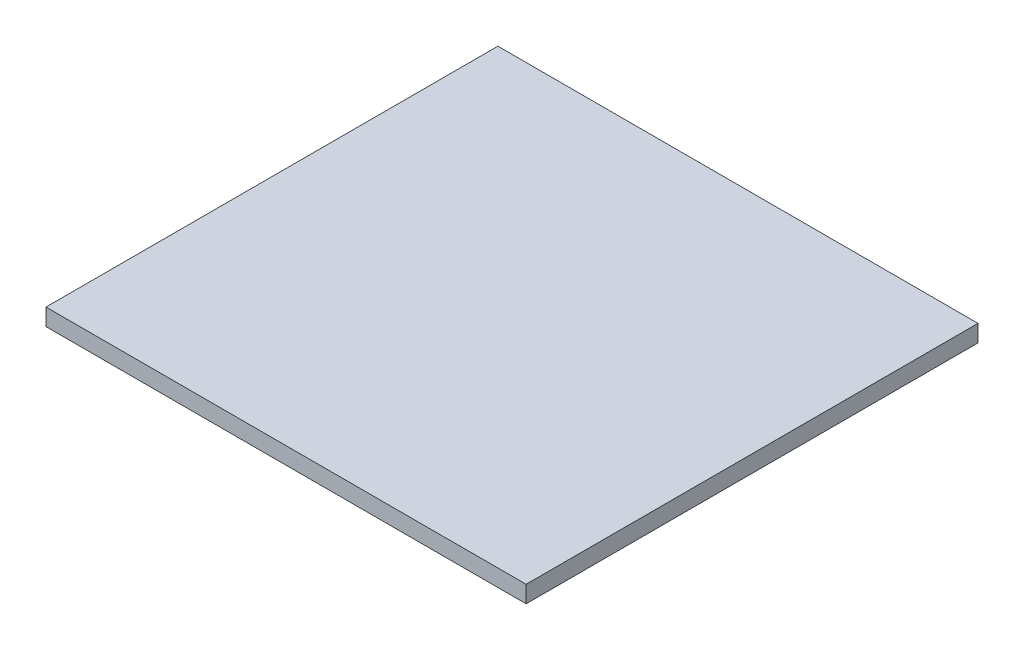
SolidWorks part; units mm, degrees
ref_plane "Front Plane" through (0, 0, 0) normal (0, 0, 1) x (1, 0, 0)
ref_plane "Top Plane" through (0, 0, 0) normal (0, 1, 0) x (1, 0, 0)
ref_plane "Right Plane" through (0, 0, 0) normal (1, 0, 0) x (0, 0, -1)
sketch "Sketch1" plane through (0, 0, 0) normal (0, 1, 0) x (1, 0, 0)
  line L1 (42.5, 40) -> (-42.5, 40)
  line L2 (42.5, 40) -> (42.5, -40)
  line L3 (42.5, -40) -> (-42.5, -40)
  line L4 (-42.5, 40) -> (-42.5, -40)
  line L5 (42.5, 40) -> (-42.5, -40) construction
  line L6 (42.5, -40) -> (-42.5, 40) construction
  point P0 (0, 0)
  dimension "D1" = 85
  dimension "D2" = 80
extrude "Boss-Extrude1" add sketch "Sketch1" along normal blind 3
